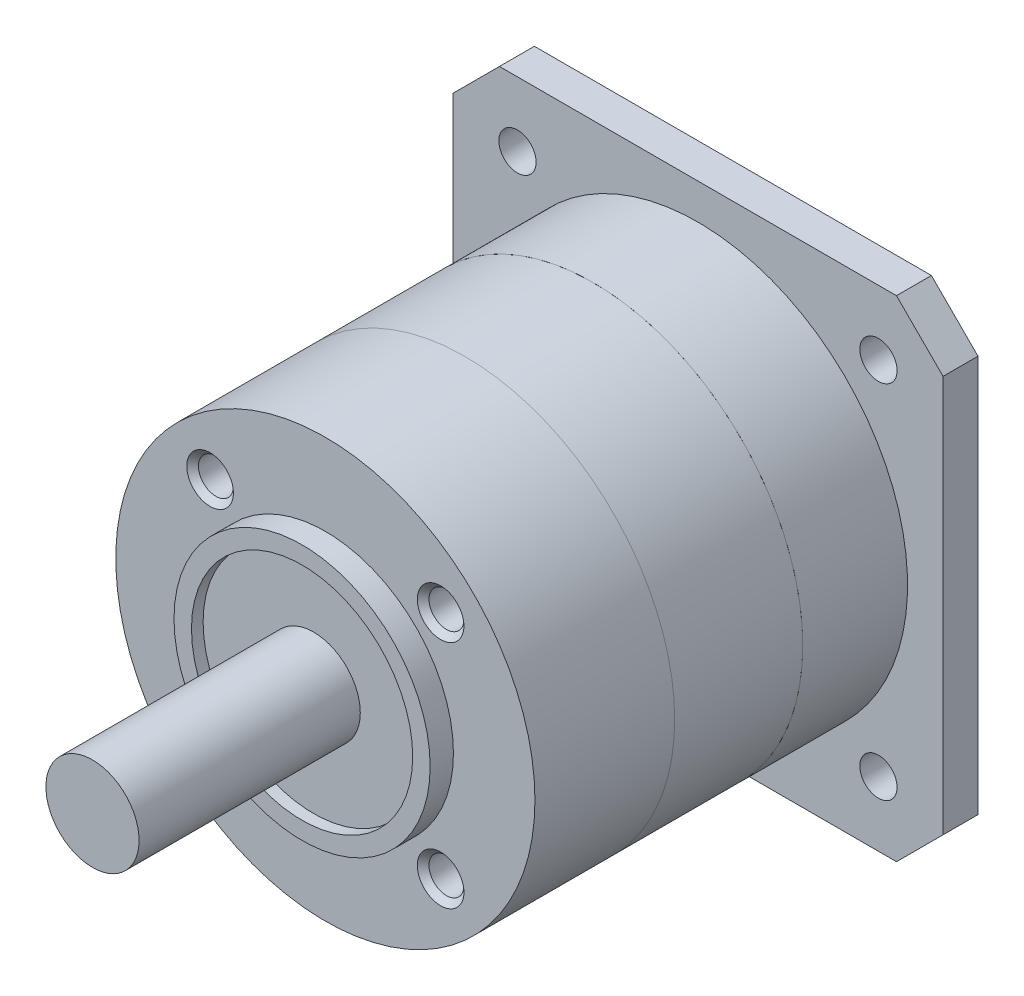
SolidWorks part; units mm, degrees
material "AISI 1020"
ref_plane "Front Plane" through (0, 0, 0) normal (0, 0, 1) x (1, 0, 0)
ref_plane "Top Plane" through (0, 0, 0) normal (0, 1, 0) x (1, 0, 0)
ref_plane "Right Plane" through (0, 0, 0) normal (1, 0, 0) x (0, 0, -1)
sketch "Sketch1" plane through (0, 0, 0) normal (0, 0, 1) x (1, 0, 0)
  line L1 (21.05, -21.05) -> (-21.05, -21.05)
  line L2 (21.05, -21.05) -> (21.05, 21.05)
  line L3 (21.05, 21.05) -> (-21.05, 21.05)
  line L4 (-21.05, -21.05) -> (-21.05, 21.05)
  line L5 (21.05, -21.05) -> (-21.05, 21.05) construction
  line L6 (21.05, 21.05) -> (-21.05, -21.05) construction
  point P0 (0, 0)
  dimension "D1" = 42.1
extrude "Boss-Extrude2" add sketch "Sketch1" along normal blind 3
sketch "Sketch3" plane through (0, 0, 3) normal (0, 0, 1) x (1, 0, 0)
  circle A0 centre (0, 0) radius 18
  dimension "D1" = 36
extrude "Boss-Extrude3" add sketch "Sketch3" along normal offset from surface (9 mm away) 12 up to face at (0, 0, 0)
sketch "Sketch4" plane through (0, 0, 12) normal (0, 0, 1) x (1, 0, 0)
  circle A1 centre (0, 0) radius 18
  circle A2 centre (0, 0) radius 18
  dimension "D1" = 0
extrude "Boss-Extrude4" add sketch "Sketch4" along normal offset from surface (11 mm away) 23 separate body up to face at (0, 0, 0)
sketch "Sketch5" plane through (0, 0, 23) normal (0, 0, 1) x (1, 0, 0)
  circle A1 centre (0, 0) radius 18
  circle A2 centre (0, 0) radius 18
  dimension "D1" = 0
extrude "Boss-Extrude5" add sketch "Sketch5" along normal offset from surface (12 mm away) 35 separate body up to face at (0, 0, 0)
sketch "Sketch6" plane through (0, 0, 35) normal (0, 0, 1) x (1, 0, 0)
  circle A0 centre (0, 0) radius 11
  circle A1 centre (0, 0) radius 9.5 construction
  dimension "D2" = 22
extrude "Boss-Extrude6" add sketch "Sketch6" along normal blind 2
sketch "Sketch9" plane through (0, 0, 37) normal (0, 0, 1) x (1, 0, 0)
  circle A3 centre (0, 0) radius 9.5
  dimension "D1" = 19
extrude "Cut-Extrude2" cut sketch "Sketch9" against normal blind 1
sketch "Sketch7" plane through (0, 0, 35) normal (0, 0, 1) x (1, 0, 0)
  circle A0 centre (0, 0) radius 4
  dimension "D1" = 8
extrude "Boss-Extrude7" add sketch "Sketch7" along normal blind 20 separate body
sketch "Sketch10" plane through (0, 0, 0) normal (0, 0, -1) x (-1, 0, 0)
  line L1 (15.5, -15.5) -> (-15.5, -15.5) construction
  line L2 (15.5, -15.5) -> (15.5, 15.5) construction
  line L3 (15.5, 15.5) -> (-15.5, 15.5) construction
  line L4 (-15.5, -15.5) -> (-15.5, 15.5) construction
  line L5 (15.5, -15.5) -> (-15.5, 15.5) construction
  line L6 (15.5, 15.5) -> (-15.5, -15.5) construction
  circle A0 centre (-15.5, 15.5) radius 1.6
  circle A1 centre (15.5, 15.5) radius 1.6
  circle A2 centre (15.5, -15.5) radius 1.6
  circle A3 centre (-15.5, -15.5) radius 1.6
  point P0 (0, 0)
  dimension "D2" = 3.2
  dimension "D1" = 31
extrude "Cut-Extrude3" cut sketch "Sketch10" against normal up to next (3 mm away)
sketch "Sketch12" plane through (0, 0, 35) normal (0, 0, 1) x (1, 0, 0)
  line L1 (9.8995, -9.8995) -> (-9.8995, -9.8995) construction
  line L2 (9.8995, -9.8995) -> (9.8995, 9.8995) construction
  line L3 (9.8995, 9.8995) -> (-9.8995, 9.8995) construction
  line L4 (-9.8995, -9.8995) -> (-9.8995, 9.8995) construction
  line L5 (9.8995, -9.8995) -> (-9.8995, 9.8995) construction
  line L6 (9.8995, 9.8995) -> (-9.8995, -9.8995) construction
  circle A0 centre (-9.8995, 9.8995) radius 1.5
  circle A1 centre (9.8995, 9.8995) radius 1.5
  circle A2 centre (9.8995, -9.8995) radius 1.5
  circle A3 centre (-9.8995, -9.8995) radius 1.5
  point P0 (0, 0)
  dimension "D1" = 3
  dimension "D2" = 28
extrude "Cut-Extrude5" cut sketch "Sketch12" against normal blind 10
chamfer "Chamfer1" distance 4 angle 45 4 edges at (21.05, -21.05, 1.5) (-21.05, -21.05, 1.5) (21.05, 21.05, 1.5) (-21.05, 21.05, 1.5)
chamfer "Chamfer2" distance 0.5 angle 45 4 edges at (-8.3995, -9.8995, 35) (11.3995, -9.8995, 35) (11.3995, 9.8995, 35) (-8.3995, 9.8995, 35)
sketch "Sketch15" plane through (0, 0, 0) normal (0, 0, -1) x (-1, 0, 0)
  circle A0 centre (0, 0) radius 11
  dimension "D1" = 22
extrude "Cut-Extrude8" cut sketch "Sketch15" against normal blind 1.5
